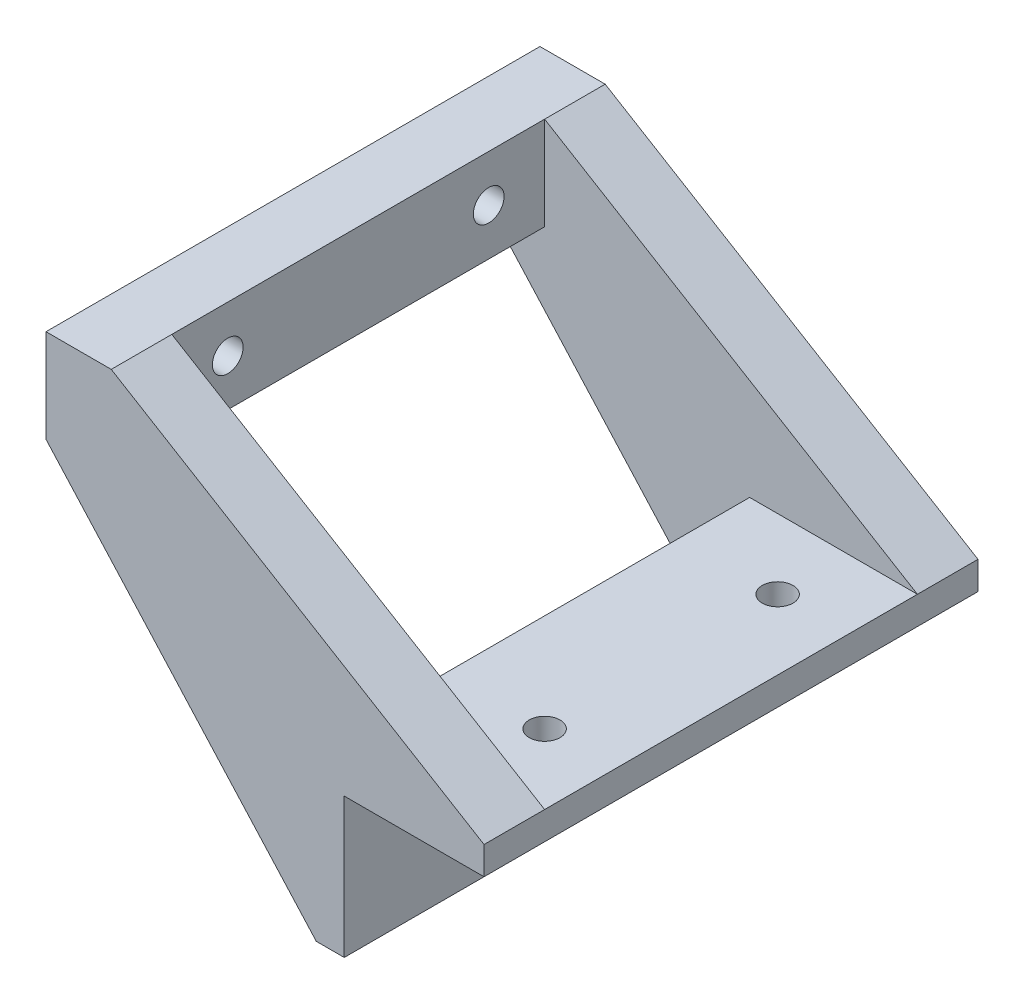
SolidWorks part; units mm, degrees
ref_plane "Front Plane" through (0, 0, 0) normal (0, 0, 1) x (1, 0, 0)
ref_plane "Top Plane" through (0, 0, 0) normal (0, 1, 0) x (1, 0, 0)
ref_plane "Right Plane" through (0, 0, 0) normal (1, 0, 0) x (0, 0, -1)
sketch "Sketch1" plane through (0, 0, 0) normal (0, 0, 1) x (1, 0, 0)
  line L0 (15, 0) -> (0, 0)
  line L1 (0, 0) -> (0, -15)
  line L2 (0, -15) -> (-3, -15)
  line L3 (-3, -15) -> (-3, 3) construction
  line L4 (-3, 3) -> (15, 3) construction
  line L5 (15, 3) -> (15, 0)
  line L6 (-25, 17.15) -> (-25, 27.15)
  line L8 (-25, 27.15) -> (15, 3)
  line L9 (-25, 17.15) -> (-32, 17.15)
  line L10 (-32, 17.15) -> (-3, -15)
  point P3 (-25, 22.15)
  dimension "D1" = 3
  dimension "D2" = 15
  dimension "D3" = 15
  dimension "D4" = 22.15
  dimension "D5" = 25
  dimension "D6" = 10
  dimension "D7" = 7
extrude "Boss-Extrude1" add sketch "Sketch1" along normal mid plane 53
sketch "Sketch3" plane through (-25, 0, 0) normal (-1, 0, 0) x (0, 0, 1)
  line L0 (-26.5, 22.15) -> (-14, 22.15) construction
  line L1 (-26.5, 27.15) -> (26.5, 27.15)
  line L2 (-26.5, 27.15) -> (-26.5, 17.15)
  line L3 (-26.5, 17.15) -> (26.5, 17.15)
  line L4 (26.5, 27.15) -> (26.5, 17.15)
  line L5 (-14, 22.15) -> (14, 22.15) construction
  line L6 (14, 22.15) -> (26.5, 22.15) construction
  line L7 (26.5, 17.15) -> (-26.5, 17.15) construction
  line L8 (26.5, 27.15) -> (26.5, 17.15) construction
  circle A0 centre (-14, 22.15) radius 1.65
  circle A1 centre (14, 22.15) radius 1.65
  dimension "D2" = 3.3
  dimension "D1" = 28
extrude "Boss-Extrude2" add sketch "Sketch3" along normal blind 7
sketch "Sketch4" plane through (15, 0, 0) normal (1, 0, 0) x (0, 0, -1)
  line L0 (-26.5, 3) -> (26.5, 3) construction
  line L2 (-20, 3) -> (-20, 27.15)
  line L5 (-26.5, 27.15) -> (26.5, 27.15) construction
  line L6 (-26.5, 27.15) -> (-20, 27.15) construction
  line L10 (20, 3) -> (20, 27.15)
  line L11 (-20, 27.15) -> (20, 27.15)
  line L12 (20, 27.15) -> (26.5, 27.15) construction
  line L13 (20, 3) -> (-20, 3)
  dimension "D1" = 40
extrude "Cut-Extrude1" cut sketch "Sketch4" against normal up to surface (40 mm away) up to face at (-25, 20.5, -14)
sketch "Sketch5" plane through (0, -15, 0) normal (0, -1, 0) x (1, 0, 0)
  line L0 (-3, 26.5) -> (-3, -26.5) construction
  line L1 (-48, -20) -> (-3, -20)
  line L5 (-25, 20) -> (-19.2364, 20) construction
  line L8 (-48, 20) -> (-3, 20)
  line L11 (-19.2364, -20) -> (-25, -20) construction
  line L13 (-48, 20) -> (-48, -20)
  line L14 (-3, 20) -> (-3, -20)
  dimension "D1" = 45
extrude "Cut-Extrude2" cut sketch "Sketch5" against normal up to vertex (62.8125 mm away)
sketch "Sketch7" plane through (0, 0, 0) normal (1, 0, 0) x (0, 0, -1)
  line L0 (0, 0) -> (0, -15) construction
  line L1 (-26.5, -15) -> (26.5, -15) construction
  line L2 (0, -7.5) -> (5, -7.5) construction
  line L3 (0, -7.5) -> (-5, -7.5) construction
  circle A0 centre (-5, -7.5) radius 1.65
  circle A1 centre (5, -7.5) radius 1.65
  dimension "D2" = 3.3
  dimension "D1" = 10
extrude "Cut-Extrude4" cut sketch "Sketch7" against normal up to surface (3 mm away) up to face at (-3, -6, 0)
sketch "Sketch8" plane through (0, 0, 0) normal (0, -1, 0) x (1, 0, 0)
  line L0 (7.5, 12.5) -> (7.5, 0) construction
  line L1 (7.5, 0) -> (7.5, -12.5) construction
  line L2 (0, 0) -> (15, 0) construction
  line L3 (15, 26.5) -> (15, -26.5) construction
  circle A0 centre (7.5, 12.5) radius 1.65
  circle A1 centre (7.5, -12.5) radius 1.65
  dimension "D2" = 3.3
  dimension "D1" = 25
extrude "Cut-Extrude5" cut sketch "Sketch8" against normal up to surface (3 mm away) up to face at (6, 3, 0)
sketch "Sketch9" plane through (-9.1144, -8.2214, 0) normal (-0.7425, -0.6698, 0) x (0, 0, 1)
  line L1 (-20, 34.1681) -> (20, 34.1681)
  line L2 (-20, 34.1681) -> (-20, 29.4795)
  line L3 (-20, 29.4795) -> (20, 29.4795)
  line L4 (20, 34.1681) -> (20, 29.4795)
extrude "Boss-Extrude3" add sketch "Sketch9" against normal up to surface
